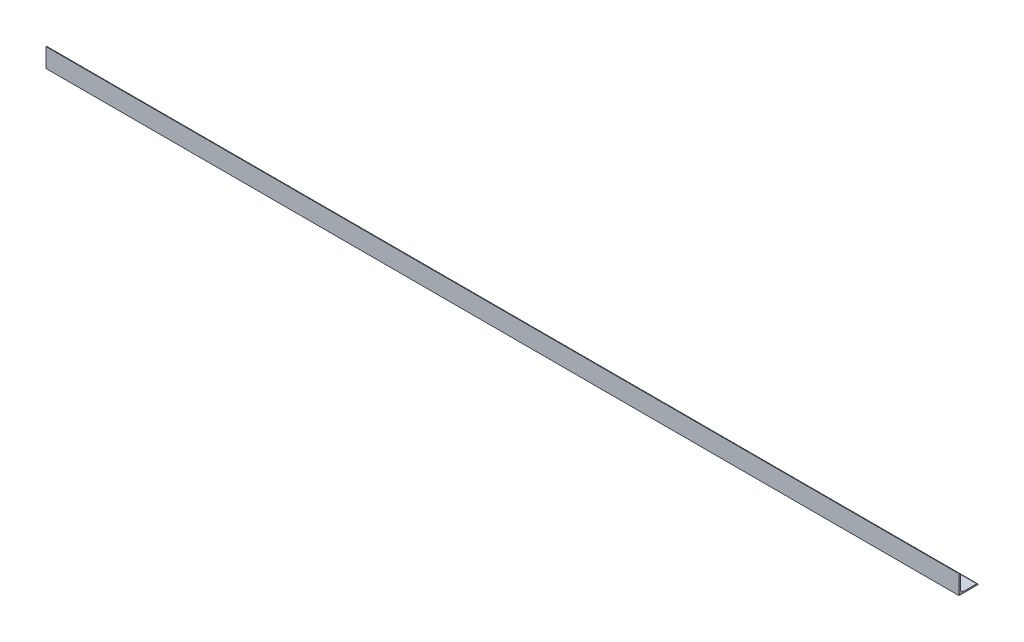
SolidWorks part; units mm, degrees
ref_plane "Front Plane" through (0, 0, 0) normal (0, 0, 1) x (1, 0, 0)
ref_plane "Top Plane" through (0, 0, 0) normal (0, 1, 0) x (1, 0, 0)
ref_plane "Right Plane" through (0, 0, 0) normal (1, 0, 0) x (0, 0, -1)
sketch "Sketch1" plane through (0, 0, 0) normal (0, 1, 0) x (1, 0, 0)
  line L0 (0, 0) -> (1920, 0)
  dimension "D1" = 1920
other "L angle (equal) 40X40X3(2)"
ref_plane "Plane1" through (0, 0, 0) normal (1, 0, 0) x (0, 0, -1)
sketch "Sketch13" plane through (0, 0, 0) normal (1, 0, 0) x (0, 0, -1)
  line L0 (0, 40) -> (0, 0)
  line L2 (3, 37) -> (3, 9)
  line L3 (9, 3) -> (37, 3)
  line L5 (40, 0) -> (0, 0)
  arc A0 (3, 37) -> (0, 40) centre (0, 37) ccw
  arc A1 (40, 0) -> (37, 3) centre (37, 0) ccw
  arc A2 (9, 3) -> (3, 9) centre (9, 9) cw
  point P8 (0, 20)
  point P9 (20, 0)
  point P10 (0, 0)
  dimension "Radius_2" = 3
  dimension "Radius_1" = 6
  dimension "V_leg" = 40
  dimension "H_leg" = 40
  dimension "thickness" = 3
